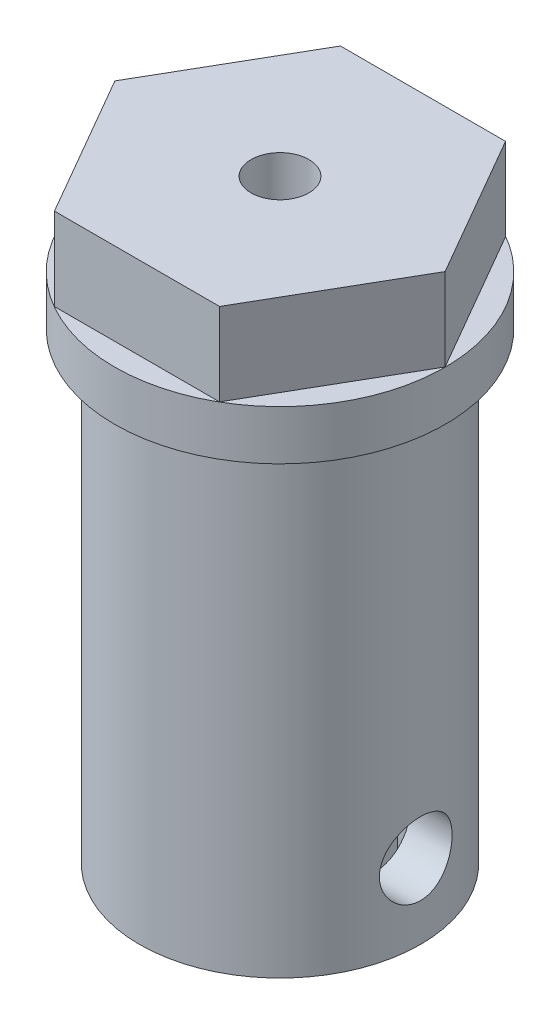
SolidWorks part; units mm, degrees
ref_plane "Спереди" through (0, 0, 0) normal (0, 0, 1) x (1, 0, 0)
ref_plane "Сверху" through (0, 0, 0) normal (0, 1, 0) x (1, 0, 0)
ref_plane "Справа" through (0, 0, 0) normal (1, 0, 0) x (0, 0, -1)
sketch "Эскиз1" plane through (0, 0, 0) normal (0, 1, 0) x (1, 0, 0)
  circle A0 centre (0, 0) radius 8.5
  dimension "D1" = 17
extrude "тело" add sketch "Эскиз1" along normal blind 28
sketch "Эскиз2" plane through (0, 28, 0) normal (0, 1, 0) x (1, 0, 0)
  circle A0 centre (0, 0) radius 10
  dimension "D1" = 20
extrude "выступ к колесу" add sketch "Эскиз2" along normal blind 3
sketch "Эскиз3" plane through (0, 31, 0) normal (0, 1, 0) x (1, 0, 0)
  line L1 (9.9882, 0) -> (4.9941, 8.65)
  line L2 (4.9941, 8.65) -> (-4.9941, 8.65)
  line L3 (-4.9941, 8.65) -> (-9.9882, 0)
  line L4 (-9.9882, 0) -> (-4.9941, -8.65)
  line L5 (-4.9941, -8.65) -> (4.9941, -8.65)
  line L6 (4.9941, -8.65) -> (9.9882, 0)
  circle A0 centre (0, 0) radius 8.65 construction
  dimension "D1" = 17.3
extrude "шестигранник" add sketch "Эскиз3" along normal blind 5
sketch "Эскиз4" plane through (0, 0, 0) normal (0, -1, 0) x (1, 0, 0)
  circle A0 centre (0, 0) radius 3.15
  dimension "D1" = 6.3
extrude "отверстие для вала двигателя" cut sketch "Эскиз4" against normal blind 12
sketch "Эскиз5" plane through (0, 0, 0) normal (0, -1, 0) x (1, 0, 0)
  line L0 (0, 0) -> (4.5, 0) construction
  line L1 (0, 0) -> (-2.25, -3.8971) construction
  line L2 (3.35, 3.75) -> (5.65, -3.75) construction
  line L3 (3.35, 3.75) -> (5.65, 3.75)
  line L4 (3.35, 3.75) -> (3.35, -3.75)
  line L5 (3.35, -3.75) -> (5.65, -3.75)
  line L6 (5.65, 3.75) -> (5.65, -3.75)
  line L7 (5.65, 3.75) -> (3.35, -3.75) construction
  line L8 (-4.9226, -1.0262) -> (1.5726, -4.7762)
  line L9 (-4.9226, -1.0262) -> (-6.0726, -3.018)
  line L10 (1.5726, -4.7762) -> (0.4226, -6.768)
  line L11 (-6.0726, -3.018) -> (0.4226, -6.768)
  line L12 (-6.0726, -3.018) -> (1.5726, -4.7762) construction
  line L13 (-4.9226, -1.0262) -> (0.4226, -6.768) construction
  point P8 (4.5, 0)
  point P9 (0, 0)
  point P12 (-2.25, -3.8971)
  point P15 (-2.5421, -5.9469)
  dimension "D1" = 4.5
  dimension "D2" = 2.3
  dimension "D3" = 7.5
  dimension "D4" = 120
extrude "углубление для гаек" cut sketch "Эскиз5" against normal blind 10
sketch "Эскиз6" plane through (3.35, 0, 0) normal (1, 0, 0) x (0, 0, -1)
  line L0 (0, 0) -> (0, 4.5) construction
  circle A0 centre (0, 4.5) radius 2.2
  dimension "D1" = 4.4
  dimension "D2" = 4.5
extrude "отверстие чтоб прикрутить 1" cut sketch "Эскиз6" along normal through all and the other way up to surface other way up to face at (0, 12, -3.15)
sketch "Эскиз7" plane through (-1.675, 0, -2.9012) normal (-0.5, 0, -0.866) x (-0.866, 0, 0.5)
  line L0 (0, 0) -> (0, 4.5) construction
  circle A0 centre (0, 4.5) radius 2.2
  dimension "D1" = 4.4
  dimension "D2" = 4.5
extrude "отверстие чтоб прикрутить 2" cut sketch "Эскиз7" along normal through all and the other way up to surface other way up to face at (0, 12, -3.15)
sketch "Эскиз10" plane through (0, 36, 0) normal (0, 1, 0) x (1, 0, 0)
  circle A0 centre (0, 0) radius 1.75
  dimension "D1" = 3.5
extrude "отверстие для шурупа" cut sketch "Эскиз10" against normal through all
